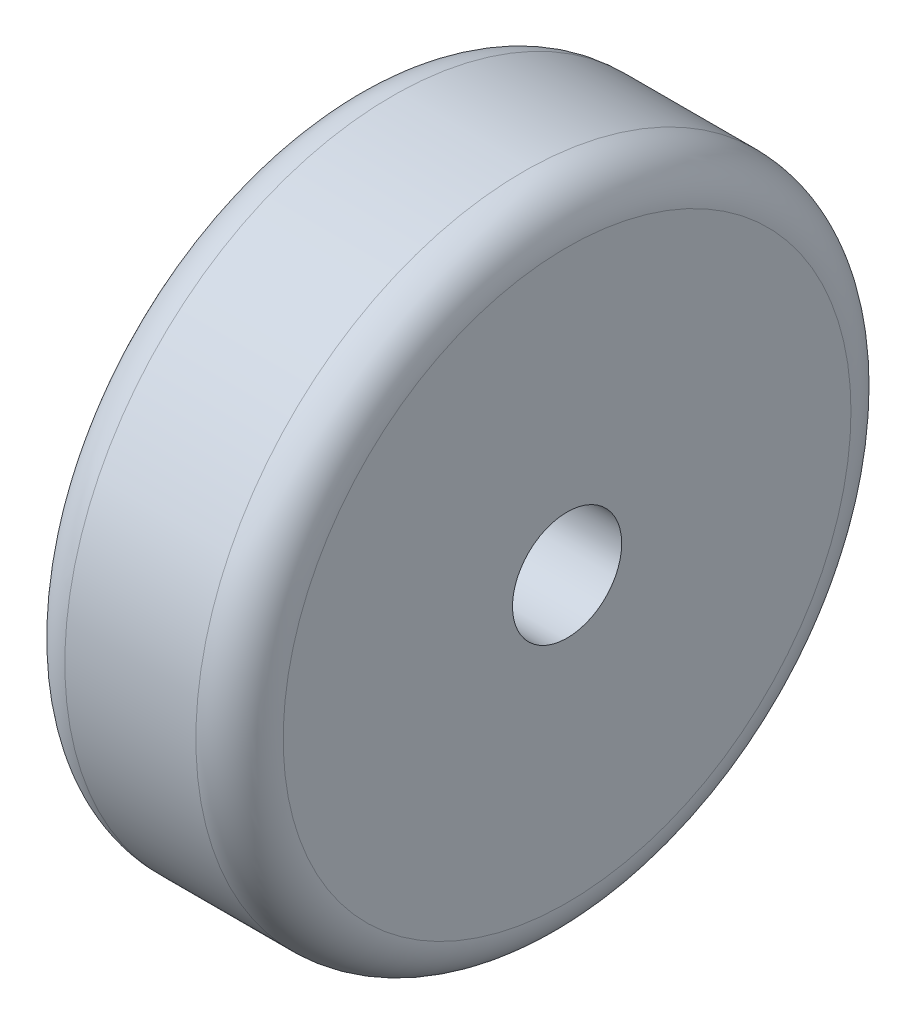
SolidWorks part; units mm, degrees
material "Silicon Rubber"
ref_plane "Front Plane" through (0, 0, 0) normal (0, 0, 1) x (1, 0, 0)
ref_plane "Top Plane" through (0, 0, 0) normal (0, 1, 0) x (1, 0, 0)
ref_plane "Right Plane" through (0, 0, 0) normal (1, 0, 0) x (0, 0, -1)
sketch "Sketch1" plane through (0, 0, 0) normal (1, 0, 0) x (0, 0, -1)
  circle A0 centre (0, 0) radius 38.1
  circle A1 centre (0, 0) radius 6.35
  dimension "D1" = 76.2
  dimension "D2" = 12.7
extrude "Boss-Extrude1" add sketch "Sketch1" along normal blind 25.4
fillet "Fillet1" radius 5.08 2 edges at (0, 0, -38.1) (25.4, 0, -38.1)
